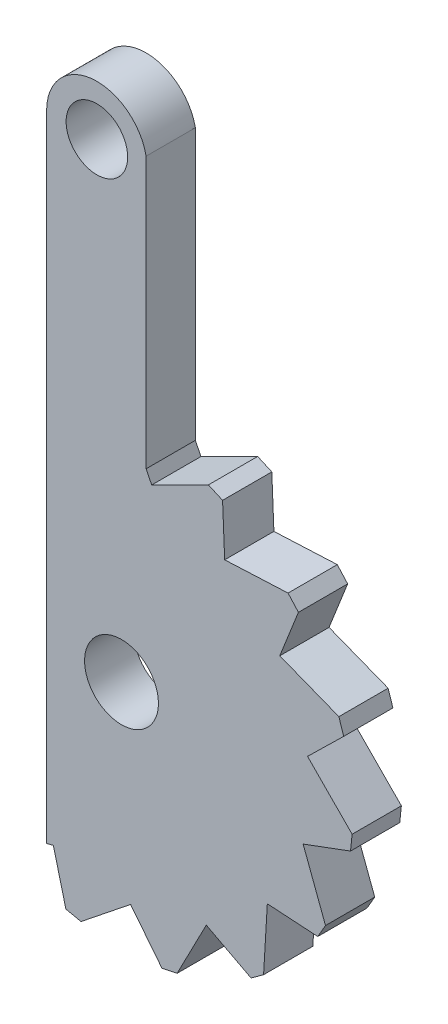
SolidWorks part; units mm, degrees
ref_plane "Front Plane" through (0, 0, 0) normal (0, 0, 1) x (1, 0, 0)
ref_plane "Top Plane" through (0, 0, 0) normal (0, 1, 0) x (1, 0, 0)
ref_plane "Right Plane" through (0, 0, 0) normal (1, 0, 0) x (0, 0, -1)
sketch "Sketch1" plane through (0, 0, 0) normal (0, 0, 1) x (1, 0, 0)
  line L0 (0, 0) -> (0, 5476.8163) construction
  line L1 (0, 0) -> (-5476.8163, 0) construction
  line L3 (-2.1097, 7.1972) -> (-0.3145, 9.3853)
  line L4 (1.3065, 7.3853) -> (0.3145, 9.3853)
  line L5 (-0.3145, 9.3853) -> (0.3145, 9.3853)
  line L6 (4.1974, 6.2154) -> (4.1047, 8.446)
  line L7 (3.53, 8.7018) -> (4.1047, 8.446)
  line L8 (1, 7.433) -> (3.53, 8.7018)
  line L9 (6.3626, 3.9708) -> (7.1851, 6.0463)
  line L10 (6.7642, 6.5137) -> (7.1851, 6.0463)
  line L11 (3.9368, 6.3837) -> (6.7642, 6.5137)
  line L12 (7.4276, 1.0396) -> (9.0232, 2.6011)
  line L13 (8.8288, 3.1993) -> (9.0232, 2.6011)
  line L14 (6.193, 4.2305) -> (8.8288, 3.1993)
  line L15 (7.2083, -2.0713) -> (9.301, -1.2938)
  line L16 (9.3668, -0.6683) -> (9.301, -1.2938)
  line L17 (7.3783, 1.3459) -> (9.3668, -0.6683)
  line L18 (5.7426, -4.8241) -> (7.9707, -4.965)
  line L19 (8.2852, -4.4203) -> (7.9707, -4.965)
  line L20 (7.2878, -1.7715) -> (8.2852, -4.4203)
  line L21 (3.284, -6.7428) -> (5.2621, -7.7778)
  line L22 (5.771, -7.408) -> (5.2621, -7.7778)
  line L23 (5.9372, -4.5825) -> (5.771, -7.408)
  line L24 (0.2576, -7.4956) -> (1.6437, -9.2456)
  line L25 (2.2589, -9.1148) -> (1.6437, -9.2456)
  line L26 (3.56, -6.6012) -> (2.2589, -9.1148)
  line L27 (-2.8134, -6.9523) -> (-2.2589, -9.1148)
  line L28 (-1.6437, -9.2456) -> (-2.2589, -9.1148)
  line L29 (0.5673, -7.4785) -> (-1.6437, -9.2456)
  line L30 (-5.398, -5.2069) -> (-5.771, -7.408)
  line L31 (-5.2621, -7.7778) -> (-5.771, -7.408)
  line L32 (-2.5236, -7.0627) -> (-5.2621, -7.7778)
  line L33 (-7.0491, -2.5612) -> (-8.2852, -4.4203)
  line L34 (-7.9707, -4.965) -> (-8.2852, -4.4203)
  line L35 (-5.178, -5.4257) -> (-7.9707, -4.965)
  line L36 (-7.4814, 0.5274) -> (-9.3668, -0.6683)
  line L37 (-9.301, -1.2938) -> (-9.3668, -0.6683)
  line L38 (-6.9372, -2.8505) -> (-9.301, -1.2938)
  line L39 (-6.6201, 3.5247) -> (-8.8288, 3.1993)
  line L40 (-9.0232, 2.6011) -> (-8.8288, 3.1993)
  line L41 (-7.4968, 0.2176) -> (-9.0232, 2.6011)
  line L42 (-4.6142, 5.9127) -> (-6.7642, 6.5137)
  line L43 (-7.1851, 6.0463) -> (-6.7642, 6.5137)
  line L44 (-6.7602, 3.248) -> (-7.1851, 6.0463)
  line L45 (-1.8103, 7.2782) -> (-3.53, 8.7018)
  line L46 (-4.1047, 8.446) -> (-3.53, 8.7018)
  line L47 (-4.8547, 5.7168) -> (-4.1047, 8.446)
  line L48 (1, 19) -> (1, 1.118)
  line L49 (-3.041, 18.6182) -> (-3.041, -7.1978)
  line L55 (0.3723, 1.4531) -> (0.3843, 1.4499)
  arc A0 (-2.1097, 7.1972) -> (-1.8103, 7.2782) centre (0, 0) ccw
  arc A1 (1, 7.433) -> (1.3065, 7.3853) centre (0, 0) ccw
  arc A2 (3.9368, 6.3837) -> (4.1974, 6.2154) centre (0, 0) ccw
  arc A3 (6.193, 4.2305) -> (6.3626, 3.9708) centre (0, 0) ccw
  arc A4 (7.3783, 1.3459) -> (7.4276, 1.0396) centre (0, 0) ccw
  arc A5 (7.2878, -1.7715) -> (7.2083, -2.0713) centre (0, 0) ccw
  arc A6 (5.9372, -4.5825) -> (5.7426, -4.8241) centre (0, 0) ccw
  arc A7 (3.56, -6.6012) -> (3.284, -6.7428) centre (0, 0) ccw
  arc A8 (0.5673, -7.4785) -> (0.2576, -7.4956) centre (0, 0) ccw
  arc A9 (-2.5236, -7.0627) -> (-2.8134, -6.9523) centre (0, 0) ccw
  arc A10 (-5.178, -5.4257) -> (-5.398, -5.2069) centre (0, 0) ccw
  arc A11 (-6.9372, -2.8505) -> (-7.0491, -2.5612) centre (0, 0) ccw
  arc A12 (-7.4968, 0.2176) -> (-7.4814, 0.5274) centre (0, 0) ccw
  arc A13 (-6.7602, 3.248) -> (-6.6201, 3.5247) centre (0, 0) ccw
  arc A14 (-4.8547, 5.7168) -> (-4.6142, 5.9127) centre (0, 0) ccw
  circle A15 centre (0, 0) radius 1.5
  arc A16 (1, 19) -> (-3.041, 18.6182) centre (-1, 18.5923) ccw
  circle A22 centre (-1, 18.5923) radius 1.25
  point P10 (0, 7.5)
  dimension "D1" = 15
  dimension "D4" = 3
  dimension "D5" = 2.5
  dimension "D6" = 11.34
  dimension "D2" = 15
  dimension "D3" = 2
extrude "Boss-Extrude2" add sketch "Sketch1" along normal blind 2
